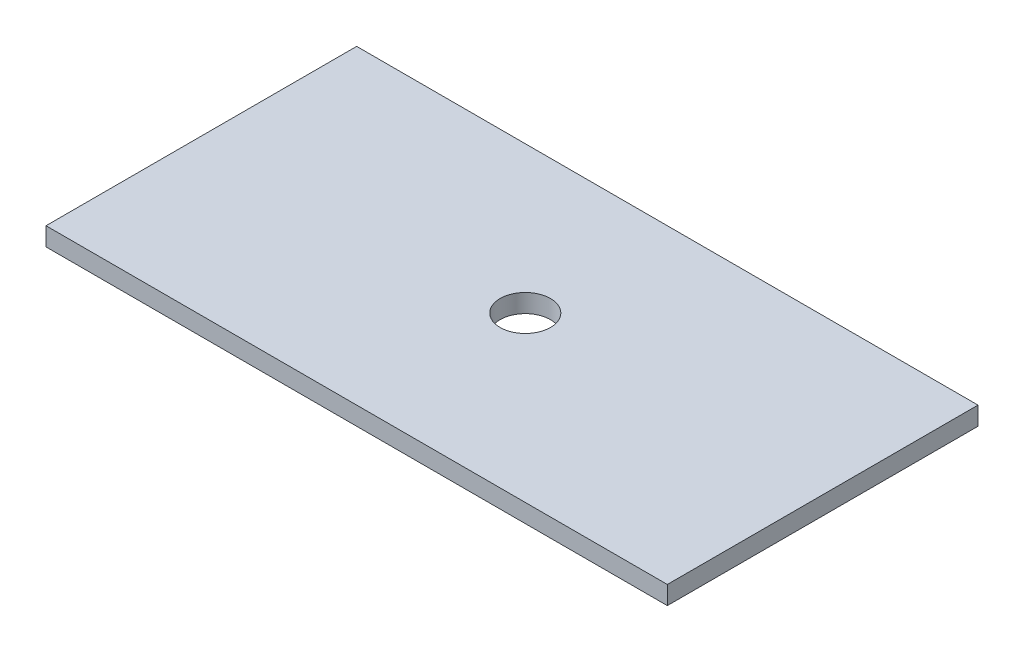
SolidWorks part; units mm, degrees
material "轻木"
ref_plane "Front" through (0, 0, 0) normal (0, 0, 1) x (1, 0, 0)
ref_plane "Top" through (0, 0, 0) normal (0, 1, 0) x (1, 0, 0)
ref_plane "Right" through (0, 0, 0) normal (1, 0, 0) x (0, 0, -1)
sketch "草图1" plane through (0, 0, 0) normal (0, 1, 0) x (1, 0, 0)
  line L1 (0, 0) -> (508, 0)
  line L2 (0, 0) -> (0, -254)
  line L3 (0, -254) -> (508, -254)
  line L4 (508, 0) -> (508, -254)
  circle A0 centre (257.7077, -119.8494) radius 20.557
  dimension "D1" = 254
  dimension "D2" = 508
extrude "凸台-拉伸1" add sketch "草图1" along normal blind 15
